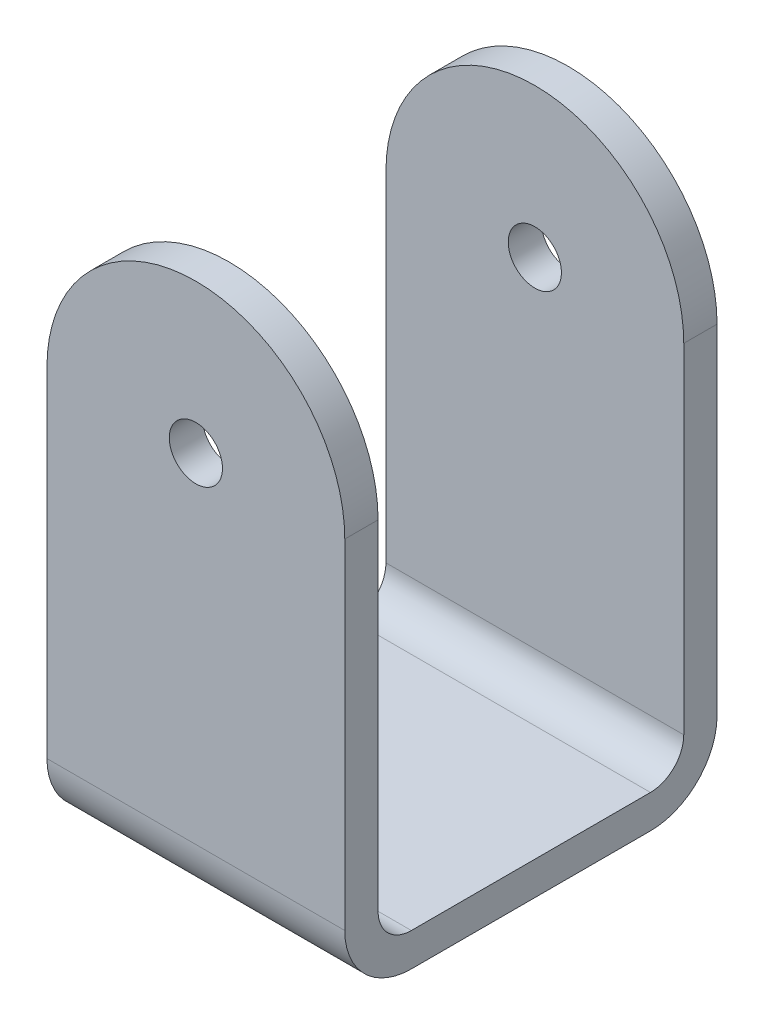
SolidWorks part; units mm, degrees
material "AISI 1020"
ref_plane "Front Plane" through (0, 0, 0) normal (0, 0, 1) x (1, 0, 0)
ref_plane "Top Plane" through (0, 0, 0) normal (0, 1, 0) x (1, 0, 0)
ref_plane "Right Plane" through (0, 0, 0) normal (1, 0, 0) x (0, 0, -1)
sketch "Sketch1" plane through (0, 0, 0) normal (0, 0, 1) x (1, 0, 0)
  line L0 (-35.56, 0) -> (-35.56, -96.8502)
  line L1 (-35.56, -96.8502) -> (35.56, -96.8502)
  line L2 (35.56, -96.8502) -> (35.56, 0)
  arc A0 (35.56, 0) -> (-35.56, 0) centre (0, 0) ccw
  circle A1 centre (0, 0) radius 6.35
  dimension "D1" = 71.12
  dimension "D2" = 12.7
  dimension "D3" = 96.8502
extrude "Boss-Extrude1" add sketch "Sketch1" along normal mid plane 88.9
sketch "Sketch2" plane through (35.56, 0, 0) normal (1, 0, 0) x (0, 0, -1)
  line L0 (-44.45, -96.8502) -> (44.45, -96.8502) construction
  line L1 (-36.4998, 50.8) -> (36.4998, 50.8)
  line L2 (-36.4998, 50.8) -> (-36.4998, -80.9498)
  line L3 (-28.5496, -88.9) -> (28.5496, -88.9)
  line L4 (36.4998, 50.8) -> (36.4998, -80.9498)
  line L5 (44.45, -96.8502) -> (44.45, 0) construction
  line L6 (-44.45, -96.8502) -> (-44.45, 0) construction
  arc A0 (28.5496, -88.9) -> (36.4998, -80.9498) centre (28.5496, -80.9498) ccw
  arc A1 (-36.4998, -80.9498) -> (-28.5496, -88.9) centre (-28.5496, -80.9498) ccw
  dimension "D5" = 7.9502
  dimension "D1" = 7.9502
  dimension "D2" = 7.9502
  dimension "D3" = 7.9502
  dimension "D4" = 50.8
extrude "Cut-Extrude1" cut sketch "Sketch2" against normal through all
fillet "Fillet1" radius 15.9004 2 edges at (0, -96.8502, -44.45) (0, -96.8502, 44.45)
